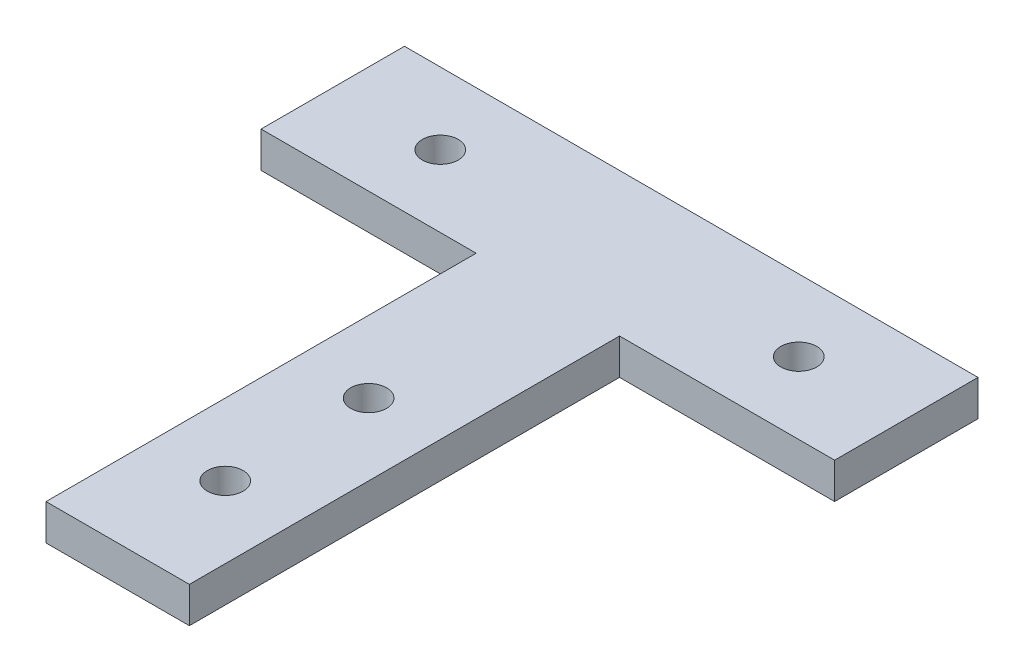
SolidWorks part; units mm, degrees
ref_plane "Front Plane" through (0, 0, 0) normal (0, 0, 1) x (1, 0, 0)
ref_plane "Top Plane" through (0, 0, 0) normal (0, 1, 0) x (1, 0, 0)
ref_plane "Right Plane" through (0, 0, 0) normal (1, 0, 0) x (0, 0, -1)
sketch "Sketch1" plane through (0, 0, 0) normal (0, 1, 0) x (1, 0, 0)
  line L0 (7.2727, -14.1414) -> (7.2727, -49.7492) construction
  line L1 (-32.7273, 5.8586) -> (47.2727, 5.8586)
  line L2 (-32.7273, 5.8586) -> (-32.7273, -14.1414)
  line L3 (-32.7273, -14.1414) -> (-2.7273, -14.1414)
  line L4 (47.2727, 5.8586) -> (47.2727, -14.1414)
  line L5 (7.2727, -14.1414) -> (7.2727, -74.1414) construction
  line L7 (-2.7273, -14.1414) -> (-2.7273, -74.1414)
  line L8 (-2.7273, -74.1414) -> (17.2727, -74.1414)
  line L9 (17.2727, -14.1414) -> (17.2727, -74.1414)
  line L10 (17.2727, -14.1414) -> (47.2727, -14.1414)
  line L11 (-32.7273, -4.1414) -> (47.2727, -4.1414) construction
  circle A0 centre (-17.7273, -4.1414) radius 2.5
  circle A2 centre (7.2727, -59.1414) radius 2.5
  circle A3 centre (7.2727, -39.1414) radius 2.5
  circle A4 centre (32.2727, -4.1414) radius 2.5
  point P19 (0, 0)
  dimension "D6" = 5
  dimension "D7" = 15
  dimension "D10" = 5
  dimension "D9" = 35
  dimension "D1" = 20
  dimension "D2" = 80
  dimension "D3" = 20
  dimension "D4" = 60
  dimension "D5" = 60
  dimension "D8" = 15
extrude "Boss-Extrude1" add sketch "Sketch1" along normal blind 5
